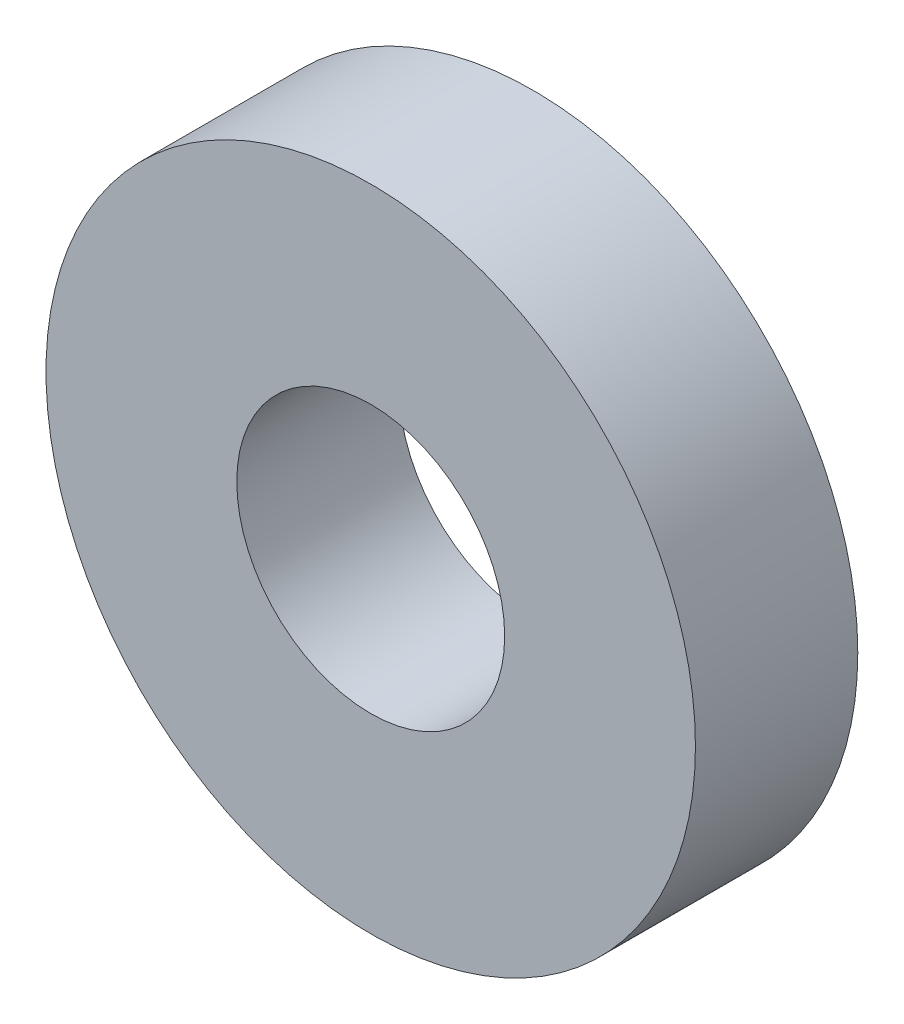
SolidWorks part; units mm, degrees
ref_plane "前视基准面" through (0, 0, 0) normal (0, 0, 1) x (1, 0, 0)
ref_plane "上视基准面" through (0, 0, 0) normal (0, 1, 0) x (1, 0, 0)
ref_plane "右视基准面" through (0, 0, 0) normal (1, 0, 0) x (0, 0, -1)
other "Configuration Table"
sketch "草图1" plane through (0, 0, 0) normal (0, 0, 1) x (1, 0, 0)
  circle A0 centre (0, 0) radius 4
  circle A1 centre (0, 0) radius 1.65
extrude "D435后支承垫片_2mm" add sketch "草图1" along normal blind 2
